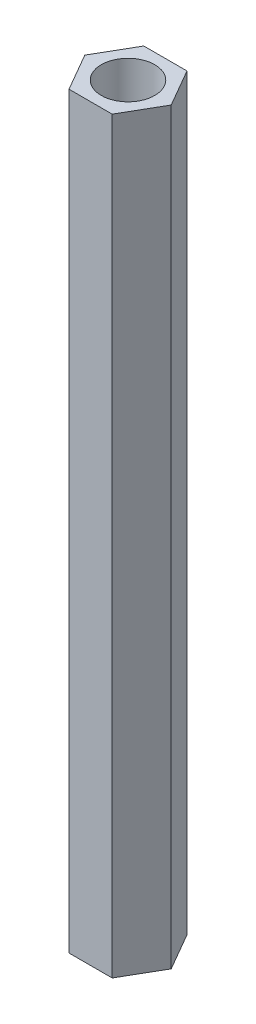
SolidWorks part; units mm, degrees
ref_plane "前视基准面" through (0, 0, 0) normal (0, 0, 1) x (1, 0, 0)
ref_plane "上视基准面" through (0, 0, 0) normal (0, 1, 0) x (1, 0, 0)
ref_plane "右视基准面" through (0, 0, 0) normal (1, 0, 0) x (0, 0, -1)
other "Configuration Table"
sketch "草图1" plane through (0, 0, 0) normal (0, 1, 0) x (1, 0, 0)
  line L7 (2.0207, -3.5) -> (4.0415, 0)
  line L8 (4.0415, 0) -> (2.0207, 3.5)
  line L9 (2.0207, 3.5) -> (-2.0207, 3.5)
  line L10 (-2.0207, 3.5) -> (-4.0415, 0)
  line L11 (-4.0415, 0) -> (-2.0207, -3.5)
  line L12 (-2.0207, -3.5) -> (2.0207, -3.5)
  circle A0 centre (0, 0) radius 2.5
  circle A1 centre (0, 0) radius 3.5 construction
  dimension "D2" = 5
  dimension "D1" = 7
extrude "凸台-拉伸1" add sketch "草图1" along normal blind 70
